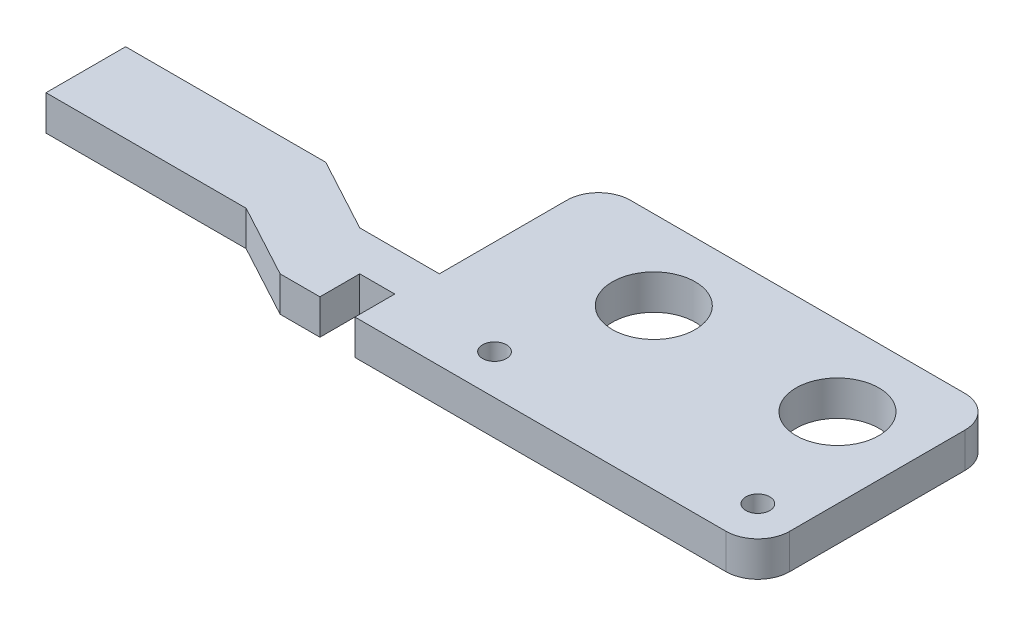
SolidWorks part; units mm, degrees
ref_plane "Front Plane" through (0, 0, 0) normal (0, 0, 1) x (1, 0, 0)
ref_plane "Top Plane" through (0, 0, 0) normal (0, 1, 0) x (1, 0, 0)
ref_plane "Right Plane" through (0, 0, 0) normal (1, 0, 0) x (0, 0, -1)
sketch "Sketch1" plane through (0, 0, 0) normal (0, 1, 0) x (1, 0, 0)
  line L0 (59.944, 0) -> (27.813, 0)
  line L1 (21.844, 6.35) -> (15.9616, 9.525)
  line L2 (0, 9.525) -> (0, 3.175)
  line L3 (0, 3.175) -> (15.9616, 3.175)
  line L4 (15.9616, 3.175) -> (21.844, 0)
  line L10 (21.844, 6.35) -> (28.194, 6.35)
  line L11 (59.944, 19.05) -> (59.944, 0)
  line L12 (28.194, 19.05) -> (59.944, 19.05)
  line L13 (28.194, 6.35) -> (28.194, 19.05)
  line L14 (25.019, 0) -> (25.019, 3.175)
  line L15 (25.019, 3.175) -> (27.813, 3.175)
  line L16 (27.813, 3.175) -> (27.813, 0)
  line L17 (25.019, 0) -> (21.844, 0)
  line L18 (0, 9.525) -> (15.9616, 9.525)
  dimension "D1" = 19.05
  dimension "D2" = 28.194
  dimension "D3" = 6.35
  dimension "D4" = 5.588
  dimension "D5" = 3.175
  dimension "D6" = 3.175
  dimension "D7" = 3.175
  dimension "D9" = 31.75
  dimension "D10" = 6.35
  dimension "D11" = 2.794
  dimension "D12" = 3.175
extrude "Boss-Extrude1" add sketch "Sketch1" along normal blind 2.794
sketch "Sketch2" plane through (0, 2.794, 0) normal (0, 1, 0) x (1, 0, 0)
  line L0 (35.769, 3.175) -> (56.769, 3.175) construction
  line L1 (59.944, 0) -> (59.944, 19.05) construction
  line L2 (27.813, 0) -> (59.944, 0) construction
  line L3 (38.944, 12.7) -> (53.594, 12.7) construction
  line L4 (46.269, 12.7) -> (46.269, 3.175) construction
  line L5 (59.944, 19.05) -> (28.194, 19.05) construction
  line L6 (59.944, 0) -> (59.944, 19.05) construction
  circle A0 centre (56.769, 3.175) radius 0.9525
  circle A1 centre (35.769, 3.175) radius 0.9525
  circle A2 centre (53.594, 12.7) radius 3.302
  circle A3 centre (38.944, 12.7) radius 3.302
  dimension "D1" = 1.905
  dimension "D5" = 6.604
  dimension "D2" = 21
  dimension "D3" = 3.175
  dimension "D4" = 3.175
  dimension "D6" = 6.35
  dimension "D7" = 6.35
extrude "Cut-Extrude1" cut sketch "Sketch2" against normal through all
fillet "Fillet2" radius 2.54 3 edges at (59.944, 1.397, 0) (59.944, 1.397, -19.05) (28.194, 1.397, -19.05)
equation "\"D1@Boss-Extrude1\"=\"thick@assy.sldasm\""
equation "\"D11@Sketch1\"=\"thick@assy.sldasm\""
